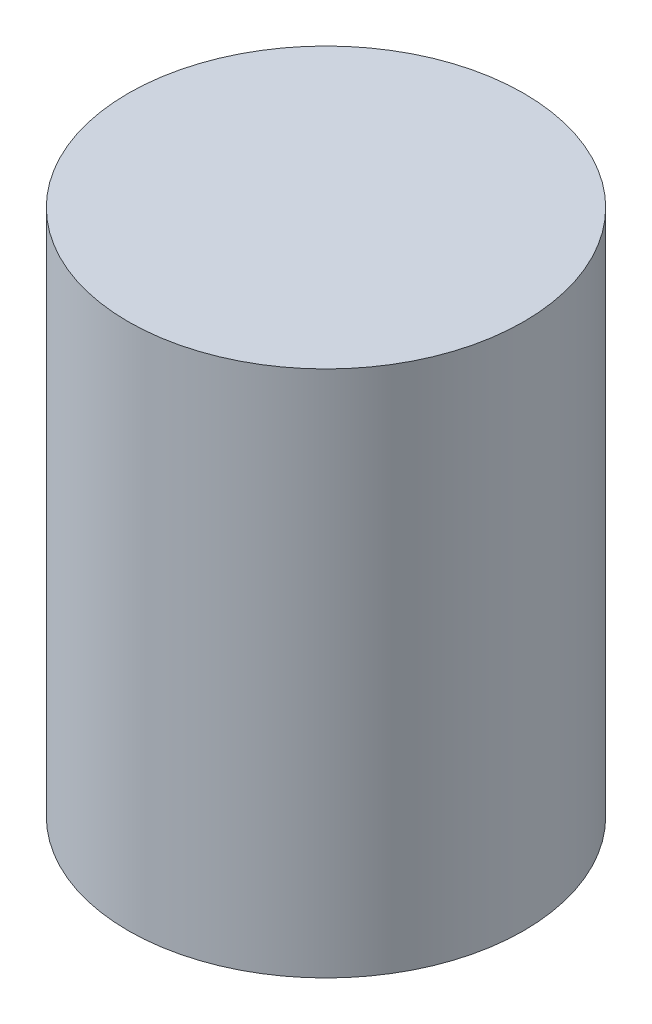
SolidWorks part; units mm, degrees
ref_plane "前视基准面" through (0, 0, 0) normal (0, 0, 1) x (1, 0, 0)
ref_plane "上视基准面" through (0, 0, 0) normal (0, 1, 0) x (1, 0, 0)
ref_plane "右视基准面" through (0, 0, 0) normal (1, 0, 0) x (0, 0, -1)
other "Configuration Table"
sketch "草图1" plane through (0, 0, 0) normal (0, 1, 0) x (1, 0, 0)
  circle A0 centre (0, 0) radius 30
  dimension "D1" = 60
extrude "凸台-拉伸1" add sketch "草图1" along normal mid plane 80
